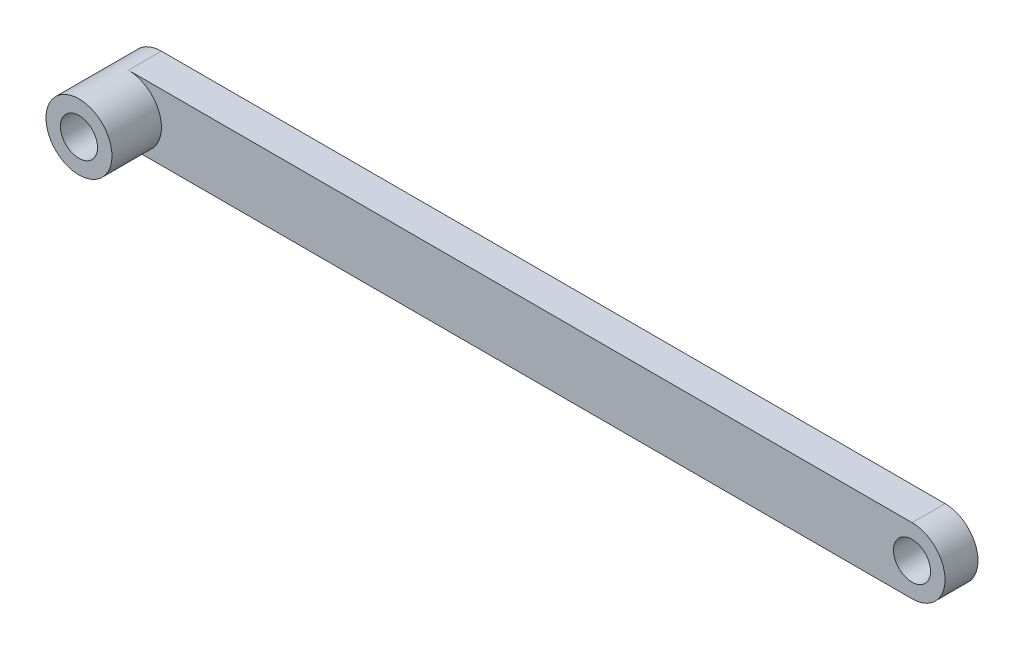
SolidWorks part; units mm, degrees
ref_plane "Front Plane" through (0, 0, 0) normal (0, 0, 1) x (1, 0, 0)
ref_plane "Top Plane" through (0, 0, 0) normal (0, 1, 0) x (1, 0, 0)
ref_plane "Right Plane" through (0, 0, 0) normal (1, 0, 0) x (0, 0, -1)
sketch "Sketch2" plane through (0, 0, 0) normal (0, 0, 1) x (1, 0, 0)
  line L0 (0, 0) -> (0, 19922.7428) construction
  line L1 (0, 0) -> (19922.7428, 0) construction
  line L2 (0, 4) -> (95, 4)
  line L3 (0, -4) -> (95, -4)
  circle A0 centre (0, 0) radius 2.25
  circle A1 centre (95, 0) radius 2.25
  arc A2 (0, 4) -> (0, -4) centre (0, 0) ccw
  arc A3 (95, -4) -> (95, 4) centre (95, 0) ccw
  dimension "D1" = 4.5
  dimension "D3" = 8
  dimension "D2" = 95
extrude "Boss-Extrude1" add sketch "Sketch2" along normal blind 10
sketch "Sketch3" plane through (0, 0, 10) normal (0, 0, 1) x (1, 0, 0)
  circle A0 centre (0, 0) radius 4
extrude "Cut-Extrude-Thin1" cut sketch "Sketch3" against normal blind 6 thin
